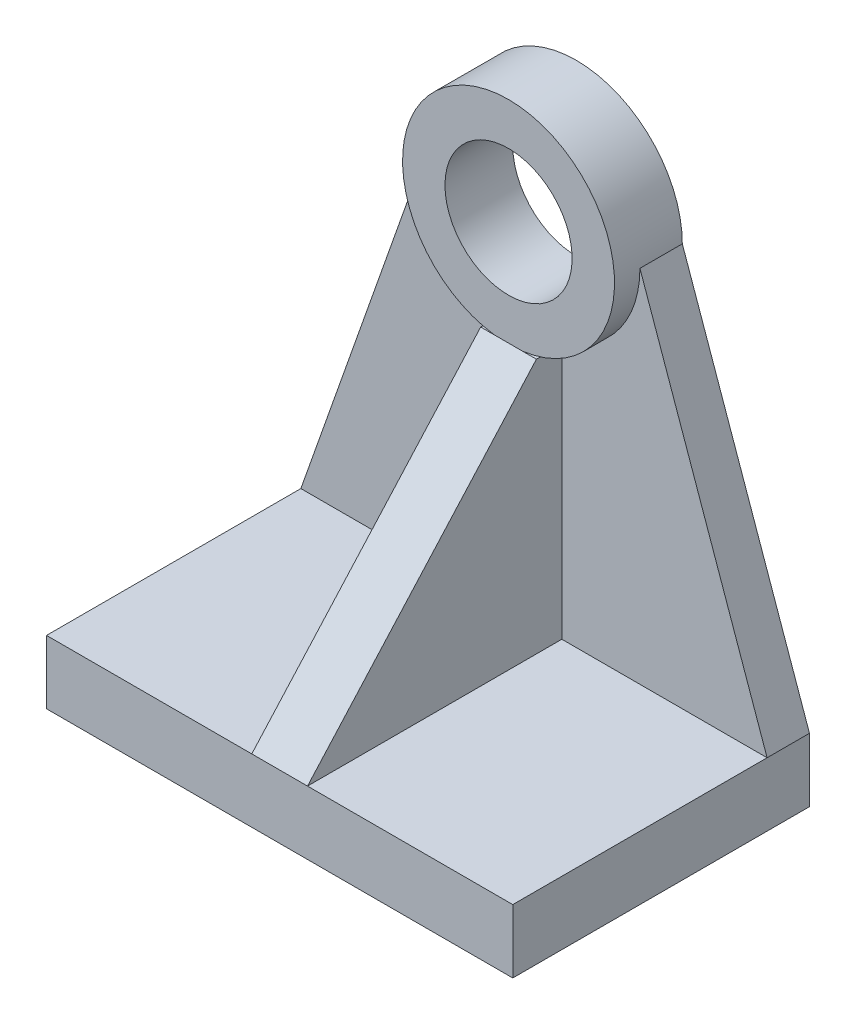
SolidWorks part; units mm, degrees
ref_plane "Front Plane" through (0, 0, 0) normal (0, 0, 1) x (1, 0, 0)
ref_plane "Top Plane" through (0, 0, 0) normal (0, 1, 0) x (1, 0, 0)
ref_plane "Right Plane" through (0, 0, 0) normal (1, 0, 0) x (0, 0, -1)
sketch "Sketch1" plane through (0, 0, 0) normal (0, 1, 0) x (1, 0, 0)
  line L1 (-69.85, -44.45) -> (69.85, -44.45)
  line L2 (-69.85, -44.45) -> (-69.85, 44.45)
  line L3 (-69.85, 44.45) -> (69.85, 44.45)
  line L4 (69.85, -44.45) -> (69.85, 44.45)
  line L5 (-69.85, -44.45) -> (69.85, 44.45) construction
  line L6 (-69.85, 44.45) -> (69.85, -44.45) construction
  point P0 (0, 0)
  dimension "D1" = 88.9
  dimension "D2" = 139.7
extrude "Boss-Extrude1" add sketch "Sketch1" along normal blind 19.05
ref_plane "Plane1" through (0, 0, -44.45) normal (0, 0, -1) x (-1, 0, 0)
sketch "Sketch2" plane through (0, 0, -44.45) normal (0, 0, -1) x (-1, 0, 0)
  line L0 (0, 0) -> (0, 171.0867) construction
  circle A0 centre (0, 127) radius 31.75
  circle A1 centre (0, 127) radius 19.05
  dimension "D2" = 38.1
  dimension "D3" = 63.5
  dimension "D1" = 127
extrude "Boss-Extrude2" add sketch "Sketch2" against normal blind 20.32 separate body
sketch "Sketch3" plane through (0, 0, -44.45) normal (0, 0, -1) x (-1, 0, 0)
  line L0 (-31.75, 127) -> (-69.85, 19.05)
  line L1 (-69.85, 19.05) -> (69.85, 19.05)
  line L2 (-69.85, 19.05) -> (69.85, 19.05) construction
  line L3 (69.85, 19.05) -> (69.85, 0) construction
  line L4 (69.85, 19.05) -> (31.75, 127)
  line L5 (-31.75, 127) -> (31.75, 127)
  circle A0 centre (0, 127) radius 31.75 construction
  circle A2 centre (0, 127) radius 31.75
  arc A3 (-31.75, 127) -> (31.75, 127) centre (0, 127) ccw
  dimension "D1" = 0
extrude "Boss-Extrude3" add sketch "Sketch3" against normal blind 12.7 contours A3 L0 L1 L4
ref_plane "Plane2" through (0, 19.05, 0) normal (0, 1, 0) x (1, 0, 0)
sketch "Sketch5" plane through (0, 19.05, 0) normal (0, 1, 0) x (1, 0, 0)
  line L0 (0, 31.75) -> (0, -44.45) construction
  line L1 (69.85, 31.75) -> (-69.85, 31.75) construction
  line L2 (-69.85, -44.45) -> (69.85, -44.45) construction
  line L3 (8.3498, 31.75) -> (8.3498, -44.45)
  line L4 (-8.3498, 31.75) -> (-8.3498, -44.45)
  line L5 (-8.3498, 31.75) -> (8.3498, 31.75)
  line L6 (-8.3498, -44.45) -> (8.3498, -44.45)
extrude "Boss-Extrude4" add sketch "Sketch5" along normal blind 76.4794
sketch "Sketch6" plane through (-8.3498, 0, 0) normal (-1, 0, 0) x (0, 0, 1)
  line L0 (-24.13, 95.5294) -> (44.45, 19.05)
  line L1 (41.91, 19.05) -> (-41.91, 19.05) construction
  line L2 (44.45, 95.5294) -> (44.45, 19.05) construction
  line L3 (44.45, 19.05) -> (44.45, 95.5294)
  line L4 (44.45, 95.5294) -> (-24.13, 95.5294)
extrude "Cut-Extrude1" cut sketch "Sketch6" against normal blind 17.018
